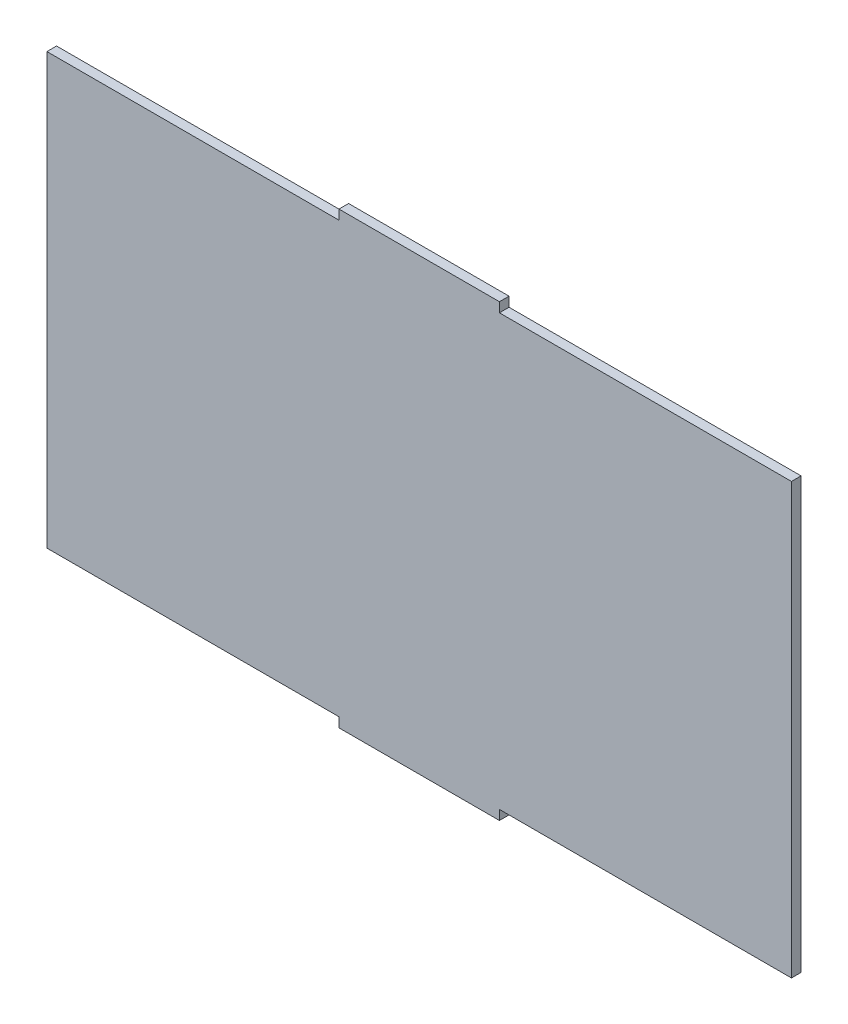
SolidWorks part; units mm, degrees
material "Teca"
ref_plane "Plano frontal" through (0, 0, 0) normal (0, 0, 1) x (1, 0, 0)
ref_plane "Plano superior" through (0, 0, 0) normal (0, 1, 0) x (1, 0, 0)
ref_plane "Plano direito" through (0, 0, 0) normal (1, 0, 0) x (0, 0, -1)
sketch "Esboço1" plane through (0, 0, 0) normal (0, 0, 1) x (1, 0, 0)
  line L0 (0, 0) -> (91, 0)
  line L1 (91, 0) -> (91, -3)
  line L2 (91, -3) -> (141, -3)
  line L3 (141, -3) -> (141, 0)
  line L4 (141, 0) -> (232, 0)
  line L5 (232, 0) -> (232, 134)
  line L6 (232, 134) -> (141, 134)
  line L7 (141, 134) -> (141, 137)
  line L8 (141, 137) -> (91, 137)
  line L9 (91, 137) -> (91, 134)
  line L10 (91, 134) -> (0, 134)
  line L11 (0, 134) -> (0, 0)
  dimension "D1" = 134
  dimension "D2" = 3
  dimension "D3" = 3
  dimension "D4" = 91
  dimension "D5" = 50
  dimension "D6" = 91
  dimension "D7" = 91
  dimension "D8" = 50
  dimension "D9" = 3
extrude "Ressalto-extrusão1" add sketch "Esboço1" along normal blind 3
